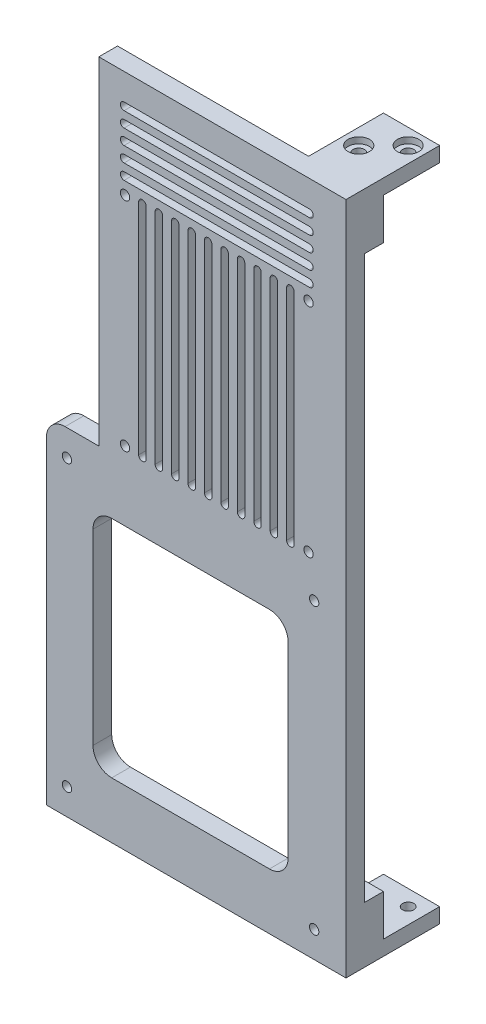
SolidWorks part; units mm, degrees
ref_plane "Alzado" through (0, 0, 0) normal (0, 0, 1) x (1, 0, 0)
ref_plane "Planta" through (0, 0, 0) normal (0, 1, 0) x (1, 0, 0)
ref_plane "Vista lateral" through (0, 0, 0) normal (1, 0, 0) x (0, 0, -1)
sketch "Croquis1" plane through (0, 0, 0) normal (0, 0, 1) x (1, 0, 0)
  line L0 (34.5, 85.0333) -> (34.5, -90) construction
  line L5 (45, -90) -> (-45, -90)
  line L6 (45, -90) -> (45, 90) construction
  line L7 (45, 90) -> (-45, 90)
  line L8 (-45, -90) -> (-45, 90)
  line L9 (45, -90) -> (-45, 90) construction
  line L10 (45, 90) -> (-45, -90)
  line L11 (-45, 85.0333) -> (45, 85.0333) construction
  line L12 (-18, 2.2833) -> (31, 2.2833) construction
  line L13 (34.5, 85.0333) -> (-21.5, 85.0333) construction
  line L14 (34.5, 85.0333) -> (34.5, 0.0333) construction
  line L15 (34.5, 0.0333) -> (-21.5, 0.0333)
  line L16 (-21.5, 85.0333) -> (-21.5, 0.0333)
  line L17 (-18, 62.7833) -> (31, 62.7833) construction
  line L18 (-16.75, 61.5333) -> (-16.75, 3.5333) construction
  line L19 (29.75, 3.5333) -> (29.75, 61.5333) construction
  line L20 (-13.3581, 61.7833) -> (-13.3581, 3.2833) construction
  line L21 (-12.3581, 61.7833) -> (-12.3581, 3.2833)
  line L22 (-14.3581, 61.7833) -> (-14.3581, 3.2833)
  line L23 (-8.9681, 61.7833) -> (-8.9681, 3.2833) construction
  line L24 (-7.9681, 61.7833) -> (-7.9681, 3.2833)
  line L25 (-9.9681, 61.7833) -> (-9.9681, 3.2833)
  line L26 (-4.5781, 61.7833) -> (-4.5781, 3.2833) construction
  line L27 (-3.5781, 61.7833) -> (-3.5781, 3.2833)
  line L28 (-5.5781, 61.7833) -> (-5.5781, 3.2833)
  line L29 (-0.1881, 61.7833) -> (-0.1881, 3.2833) construction
  line L30 (0.8119, 61.7833) -> (0.8119, 3.2833)
  line L31 (-1.1881, 61.7833) -> (-1.1881, 3.2833)
  line L32 (4.2019, 61.7833) -> (4.2019, 3.2833) construction
  line L33 (5.2019, 61.7833) -> (5.2019, 3.2833)
  line L34 (3.2019, 61.7833) -> (3.2019, 3.2833)
  line L35 (8.5919, 61.7833) -> (8.5919, 3.2833) construction
  line L36 (9.5919, 61.7833) -> (9.5919, 3.2833)
  line L37 (7.5919, 61.7833) -> (7.5919, 3.2833)
  line L38 (12.9819, 61.7833) -> (12.9819, 3.2833) construction
  line L39 (13.9819, 61.7833) -> (13.9819, 3.2833)
  line L40 (11.9819, 61.7833) -> (11.9819, 3.2833)
  line L41 (17.3719, 61.7833) -> (17.3719, 3.2833) construction
  line L42 (18.3719, 61.7833) -> (18.3719, 3.2833)
  line L43 (16.3719, 61.7833) -> (16.3719, 3.2833)
  line L44 (21.7619, 61.7833) -> (21.7619, 3.2833) construction
  line L45 (22.7619, 61.7833) -> (22.7619, 3.2833)
  line L46 (20.7619, 61.7833) -> (20.7619, 3.2833)
  line L47 (26.1519, 61.7833) -> (26.1519, 3.2833) construction
  line L48 (27.1519, 61.7833) -> (27.1519, 3.2833)
  line L49 (25.1519, 61.7833) -> (25.1519, 3.2833)
  line L50 (-45, -85) -> (45, -85) construction
  line L55 (-21.5, 85.0333) -> (34.5, 85.0333)
  line L56 (-27.5, 85.0333) -> (-35.5, 85.0333) construction
  line L57 (-27.5, 85.0333) -> (-27.5, 0) construction
  line L58 (-27.5, 0) -> (-35.5, 0) construction
  line L59 (-35.5, 85.0333) -> (-35.5, 0) construction
  line L60 (34.5, 85.0333) -> (34.5, 0.0333)
  line L61 (45, 75) -> (45, -75)
  line L62 (-35.5, -5) -> (34.5, -5) construction
  line L63 (-35.5, -5) -> (-35.5, -85) construction
  line L64 (-35.5, -85) -> (34.5, -85) construction
  line L65 (34.5, -5) -> (34.5, -85) construction
  line L66 (-35.5, -5) -> (34.5, -85) construction
  line L67 (-35.5, -85) -> (34.5, -5) construction
  line L68 (45, -90) -> (41, -90)
  line L69 (45, -90) -> (45, -75) construction
  line L70 (45, -75) -> (41, -75)
  line L71 (41, -90) -> (41, -75)
  line L72 (45, -90) -> (41, -75) construction
  line L73 (45, -75) -> (41, -90) construction
  line L78 (45, 90) -> (41, 90)
  line L79 (45, 90) -> (45, 75) construction
  line L80 (45, 75) -> (41, 75)
  line L81 (41, 90) -> (41, 75)
  line L82 (45, 90) -> (41, 75) construction
  line L83 (45, 75) -> (41, 90) construction
  line L84 (-19.25, 61.4333) -> (-19.25, 85.0333) construction
  line L85 (-19.25, 85.0333) -> (-19.25, 61.4333) construction
  line L86 (32.25, 61.5333) -> (32.25, 85.0333) construction
  line L87 (32.25, 85.0333) -> (32.25, 61.5333) construction
  line L88 (-18.25, 65.8083) -> (31.25, 65.8083) construction
  line L89 (-18.25, 66.8083) -> (31.25, 66.8083)
  line L90 (-18.25, 64.8083) -> (31.25, 64.8083)
  line L91 (-18.25, 69.8383) -> (31.25, 69.8383) construction
  line L94 (-18.25, 70.8383) -> (31.25, 70.8383)
  line L97 (-18.25, 68.8383) -> (31.25, 68.8383)
  line L100 (-18.25, 73.8683) -> (31.25, 73.8683) construction
  line L103 (-18.25, 74.8683) -> (31.25, 74.8683)
  line L104 (-18.25, 72.8683) -> (31.25, 72.8683)
  line L105 (-18.25, 77.8983) -> (31.25, 77.8983) construction
  line L106 (-18.25, 78.8983) -> (31.25, 78.8983)
  line L107 (-18.25, 76.8983) -> (31.25, 76.8983)
  line L108 (-18.25, 81.9283) -> (31.25, 81.9283) construction
  line L109 (-18.25, 82.9283) -> (31.25, 82.9283)
  line L110 (-18.25, 80.9283) -> (31.25, 80.9283)
  line L111 (-27.5, 4) -> (-27.5, 81.0333)
  line L112 (-35.5, 4) -> (-35.5, 81.0333)
  circle A0 centre (-18, 3.5333) radius 1.25
  circle A1 centre (31, 3.5333) radius 1.25
  circle A2 centre (-18, 61.5333) radius 1.25
  circle A3 centre (31, 61.5333) radius 1.25
  arc A4 (-12.3581, 61.7833) -> (-14.3581, 61.7833) centre (-13.3581, 61.7833) ccw
  arc A5 (-14.3581, 3.2833) -> (-12.3581, 3.2833) centre (-13.3581, 3.2833) ccw
  arc A6 (-7.9681, 61.7833) -> (-9.9681, 61.7833) centre (-8.9681, 61.7833) ccw
  arc A7 (-9.9681, 3.2833) -> (-7.9681, 3.2833) centre (-8.9681, 3.2833) ccw
  arc A8 (-3.5781, 61.7833) -> (-5.5781, 61.7833) centre (-4.5781, 61.7833) ccw
  arc A9 (-5.5781, 3.2833) -> (-3.5781, 3.2833) centre (-4.5781, 3.2833) ccw
  arc A10 (0.8119, 61.7833) -> (-1.1881, 61.7833) centre (-0.1881, 61.7833) ccw
  arc A11 (-1.1881, 3.2833) -> (0.8119, 3.2833) centre (-0.1881, 3.2833) ccw
  arc A12 (5.2019, 61.7833) -> (3.2019, 61.7833) centre (4.2019, 61.7833) ccw
  arc A13 (3.2019, 3.2833) -> (5.2019, 3.2833) centre (4.2019, 3.2833) ccw
  arc A14 (9.5919, 61.7833) -> (7.5919, 61.7833) centre (8.5919, 61.7833) ccw
  arc A15 (7.5919, 3.2833) -> (9.5919, 3.2833) centre (8.5919, 3.2833) ccw
  arc A16 (13.9819, 61.7833) -> (11.9819, 61.7833) centre (12.9819, 61.7833) ccw
  arc A17 (11.9819, 3.2833) -> (13.9819, 3.2833) centre (12.9819, 3.2833) ccw
  arc A18 (18.3719, 61.7833) -> (16.3719, 61.7833) centre (17.3719, 61.7833) ccw
  arc A19 (16.3719, 3.2833) -> (18.3719, 3.2833) centre (17.3719, 3.2833) ccw
  arc A20 (22.7619, 61.7833) -> (20.7619, 61.7833) centre (21.7619, 61.7833) ccw
  arc A21 (20.7619, 3.2833) -> (22.7619, 3.2833) centre (21.7619, 3.2833) ccw
  arc A22 (27.1519, 61.7833) -> (25.1519, 61.7833) centre (26.1519, 61.7833) ccw
  arc A23 (25.1519, 3.2833) -> (27.1519, 3.2833) centre (26.1519, 3.2833) ccw
  circle A24 centre (22.5, 87.5333) radius 1.25 construction
  circle A25 centre (0, 87.5333) radius 1.25 construction
  circle A26 centre (-22.5, 87.5333) radius 1.25 construction
  circle A27 centre (-22.5, -87.5) radius 1.25 construction
  circle A28 centre (0, -87.5) radius 1.25 construction
  circle A29 centre (22.5, -87.5) radius 1.25 construction
  circle A30 centre (-33.5, -7) radius 1.25
  circle A31 centre (32.5, -7) radius 1.25
  circle A32 centre (-33.5, -83) radius 1.25
  circle A33 centre (32.5, -83) radius 1.25
  arc A34 (-18.25, 66.8083) -> (-18.25, 64.8083) centre (-18.25, 65.8083) ccw
  arc A35 (31.25, 64.8083) -> (31.25, 66.8083) centre (31.25, 65.8083) ccw
  arc A44 (-18.25, 70.8383) -> (-18.25, 68.8383) centre (-18.25, 69.8383) ccw
  arc A45 (31.25, 68.8383) -> (31.25, 70.8383) centre (31.25, 69.8383) ccw
  arc A46 (-18.25, 74.8683) -> (-18.25, 72.8683) centre (-18.25, 73.8683) ccw
  arc A47 (31.25, 72.8683) -> (31.25, 74.8683) centre (31.25, 73.8683) ccw
  arc A48 (-18.25, 78.8983) -> (-18.25, 76.8983) centre (-18.25, 77.8983) ccw
  arc A49 (31.25, 76.8983) -> (31.25, 78.8983) centre (31.25, 77.8983) ccw
  arc A50 (-18.25, 82.9283) -> (-18.25, 80.9283) centre (-18.25, 81.9283) ccw
  arc A51 (31.25, 80.9283) -> (31.25, 82.9283) centre (31.25, 81.9283) ccw
  arc A52 (-27.5, 81.0333) -> (-35.5, 81.0333) centre (-31.5, 81.0333) ccw
  arc A53 (-35.5, 4) -> (-27.5, 4) centre (-31.5, 4) ccw
  point P0 (0, 0)
  point P31 (-13.3581, 32.5333)
  point P39 (-8.9681, 32.5333)
  point P46 (-4.5781, 32.5333)
  point P53 (-0.1881, 32.5333)
  point P60 (4.2019, 32.5333)
  point P67 (8.5919, 32.5333)
  point P74 (12.9819, 32.5333)
  point P81 (17.3719, 32.5333)
  point P88 (21.7619, 32.5333)
  point P95 (26.1519, 32.5333)
  point P108 (-0.5, -45)
  point P133 (43, 82.5)
  point P137 (43, -82.5)
  point P144 (6.5, 65.8083)
  point P152 (6.5, 69.8383)
  point P159 (6.5, 73.8683)
  point P166 (6.5, 77.8983)
  point P173 (6.5, 81.9283)
  dimension "D7" = 58
  dimension "D10" = 2.5
  dimension "D12" = 2
  dimension "D17" = 2.5
  dimension "D24" = 2.5
  dimension "D23" = 2.5
  dimension "D37" = 4
  dimension "D38" = 4
  dimension "D2" = 90
  dimension "D4" = 10.5
  dimension "D5" = 56
  dimension "D6" = 85
  dimension "D8" = 3.5
  dimension "D9" = 3.5
  dimension "D11" = 3.5
  dimension "D13" = 2
  dimension "D14" = 2.3919
  dimension "D15" = 3
  dimension "D18" = 2.5
  dimension "D19" = 180
  dimension "D21" = 80
  dimension "D22" = 70
  dimension "D25" = 2.5
  dimension "D27" = 22.5
  dimension "D28" = 22.5
  dimension "D29" = 22.5
  dimension "D30" = 6
  dimension "D31" = 2
  dimension "D32" = 2
  dimension "D33" = 2
  dimension "D34" = 2
  dimension "D35" = 2
  dimension "D36" = 5
  dimension "D45" = 2.025
  dimension "D16" = 7
  dimension "D20" = 3
  dimension "D26" = 3
extrude "Saliente-Extruir2" add sketch "Croquis1" along normal blind 10
sketch "Croquis2" plane through (0, -90, 0) normal (0, -1, 0) x (1, 0, 0)
  line L1 (41, 0) -> (26, 0)
  line L2 (41, 0) -> (41, -15)
  line L3 (41, -15) -> (26, -15)
  line L4 (26, 0) -> (26, -15)
  line L5 (41, 0) -> (26, -15) construction
  line L6 (41, -15) -> (26, 0) construction
  circle A0 centre (36.8, -10.8) radius 1.5
  circle A1 centre (30.2, -4.2) radius 1.5
  point P4 (33.5, -7.5)
  dimension "D1" = 4.2
  dimension "D3" = 3
  dimension "D4" = 3
  dimension "D2" = 4.2
  dimension "D5" = 15
extrude "Saliente-Extruir3" add sketch "Croquis2" against normal blind 4
sketch "Croquis3" plane through (0, -90, 0) normal (0, -1, 0) x (1, 0, 0)
  circle A0 centre (30.2, -4.2) radius 2.85
  circle A1 centre (36.8, -10.8) radius 2.85
  dimension "D1" = 5.7
  dimension "D2" = 5.7
extrude "Cortar-Extruir1" cut sketch "Croquis3" against normal blind 1.65
mirror "Simetría2" about plane through (0, 0, 0) normal (0, 1, 0) of "Cortar-Extruir1", "Saliente-Extruir3"
sketch "Croquis4" plane through (0, 75, 0) normal (0, 1, 0) x (1, 0, 0)
  line L1 (45, -10) -> (41, -10)
  line L2 (45, -10) -> (45, 0)
  line L3 (45, 0) -> (41, 0)
  line L4 (41, -10) -> (41, 0)
  line L5 (45, -10) -> (41, 0) construction
  line L6 (45, 0) -> (41, -10) construction
  point P4 (43, -5)
extrude "Cortar-Extruir2" cut sketch "Croquis4" against normal up to next
sketch "Croquis5" plane through (0, 0, 10) normal (0, 0, 1) x (1, 0, 0)
  line L1 (-45, 90) -> (-25, 90)
  line L2 (-45, 90) -> (-45, 0)
  line L3 (-39, 0) -> (-25, 0)
  line L4 (-25, 90) -> (-25, 0)
  line L5 (-45, 90) -> (-25, 0) construction
  line L6 (-45, 0) -> (-25, 90) construction
  line L7 (-45, -90) -> (-39, -90)
  line L8 (-45, -90) -> (-45, 0)
  line L10 (-39, -90) -> (-39, 0)
  line L11 (-45, -90) -> (-39, 0) construction
  line L12 (-45, 0) -> (-39, -90) construction
  point P4 (-35, 45)
  point P11 (-42, -45)
  dimension "D1" = 20
  dimension "D2" = 90
  dimension "D3" = 6
extrude "Cortar-Extruir3" cut sketch "Croquis5" against normal up to next
fillet "Redondeo1" radius 5 1 edges at (-39, 0, 5)
sketch "Croquis7" plane through (0, 0, 0) normal (0, 0, -1) x (-1, 0, 0)
  line L0 (-41, -86) -> (-41, 86) construction
  line L3 (-26, -75) -> (-41, -75)
  line L5 (-26, -86) -> (-41, -75) construction
  line L6 (-26, -75) -> (-41, -86) construction
  line L7 (39, -90) -> (39, -5) construction
  line L10 (-26, 75) -> (-41, 75)
  line L12 (-26, 86) -> (-41, 75) construction
  line L13 (-26, 75) -> (-41, 86) construction
  line L15 (-41, 75) -> (-41, -75)
  line L17 (39, 75) -> (39, -75)
  line L18 (-41, 75) -> (39, -75) construction
  line L19 (-41, -75) -> (39, 75) construction
  line L21 (-26, 90) -> (39, 90)
  line L22 (-26, 90) -> (-26, 75)
  line L24 (39, 90) -> (39, 75)
  line L25 (-26, 90) -> (39, 75) construction
  line L26 (-26, 75) -> (39, 90) construction
  line L28 (-26, -75) -> (-26, -90)
  line L29 (-26, -90) -> (39, -90)
  line L30 (39, -75) -> (39, -90)
  line L31 (-26, -75) -> (39, -90) construction
  line L32 (-26, -90) -> (39, -75) construction
  point P4 (-33.5, -80.5)
  point P12 (-33.5, 80.5)
  point P17 (-1, 0)
  point P24 (6.5, 82.5)
  point P28 (6.5, -82.5)
  dimension "D1" = 11
  dimension "D2" = 15
  dimension "D3" = 150
  dimension "D4" = 15
  dimension "D5" = 15
  dimension "D6" = 15
  dimension "D7" = 15
extrude "Cortar-Extruir5" cut sketch "Croquis7" along direction (0, 0, 1) on the side against the normal blind 5 contours L30 L17 L24 L21 L22 L10 L15 L3 L28 L29
sketch "Croquis8" plane through (0, 0, 10) normal (0, 0, 1) x (1, 0, 0)
  line L0 (-33.5, -7) -> (32.5, -83) construction
  line L1 (32.5, -83) -> (32.5, -7) construction
  line L2 (32.5, -7) -> (-33.5, -83) construction
  line L4 (25.5526, -75) -> (-26.5526, -75)
  line L5 (25.5526, -75) -> (25.5526, -15)
  line L6 (25.5526, -15) -> (-26.5526, -15)
  line L7 (-26.5526, -75) -> (-26.5526, -15)
  line L8 (25.5526, -75) -> (-26.5526, -15) construction
  line L9 (25.5526, -15) -> (-26.5526, -75) construction
  point P4 (-0.5, -45)
  dimension "D1" = 60
extrude "Cortar-Extruir6" cut sketch "Croquis8" against normal blind 5
fillet "Redondeo2" radius 5 4 edges at (-26.5526, -75, 7.5) (25.5526, -75, 7.5) (-26.5526, -15, 7.5) (25.5526, -15, 7.5)
